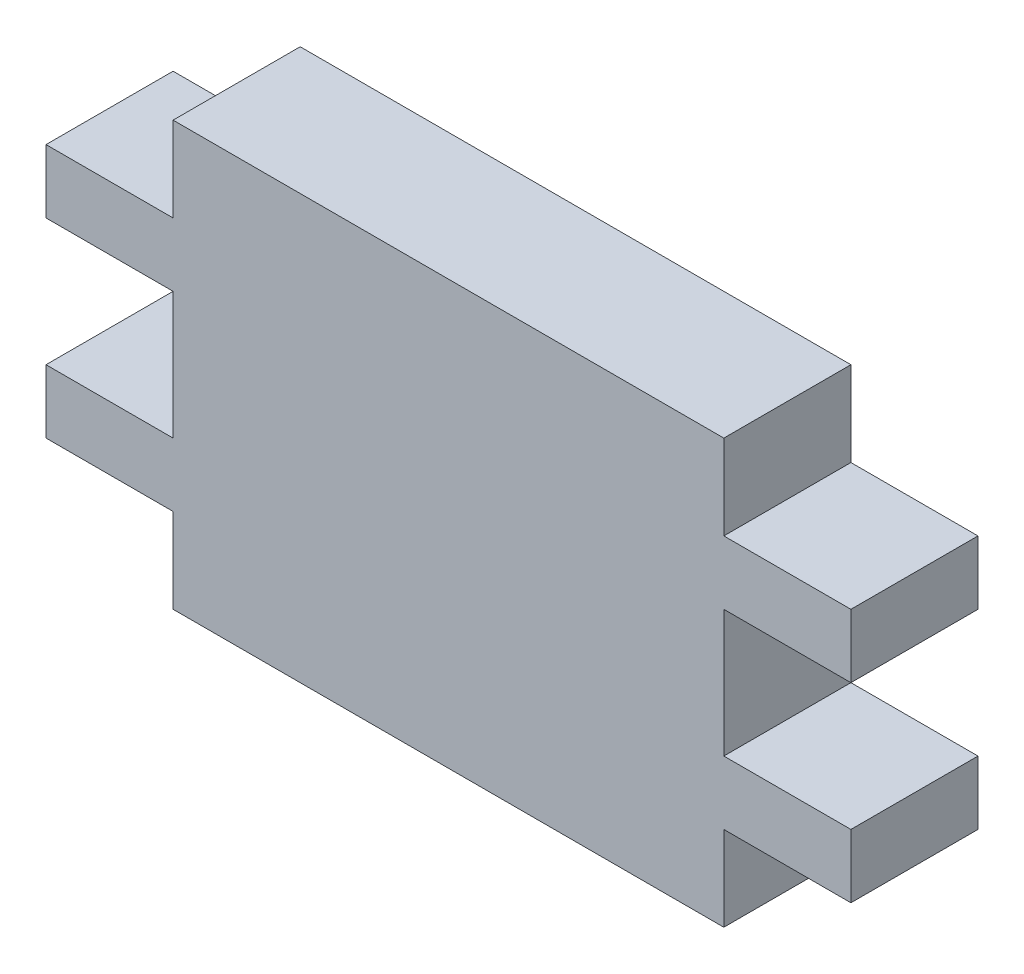
SolidWorks part; units mm, degrees
ref_plane "Plan de face" through (0, 0, 0) normal (0, 0, 1) x (1, 0, 0)
ref_plane "Plan de dessus" through (0, 0, 0) normal (0, 1, 0) x (1, 0, 0)
ref_plane "Plan de droite" through (0, 0, 0) normal (1, 0, 0) x (0, 0, -1)
sketch "Sketch1" plane through (0, 0, 0) normal (0, 0, 1) x (1, 0, 0)
  line L1 (-9.5, -5) -> (9.5, -5)
  line L2 (-9.5, -5) -> (-9.5, 5)
  line L3 (-9.5, 5) -> (9.5, 5)
  line L4 (9.5, -5) -> (9.5, 5)
  line L5 (-9.5, -5) -> (9.5, 5) construction
  line L6 (-9.5, 5) -> (9.5, -5) construction
  point P0 (0, 0)
  dimension "D1" = 19
  dimension "D2" = 10
extrude "Boss-Extrude1" add sketch "Sketch1" along normal blind 3
sketch "Sketch2" plane through (0, 0, 3) normal (0, 0, 1) x (1, 0, 0)
  line L0 (-9.5, 5) -> (-9.5, -5) construction
  line L1 (-9.5, 3) -> (-6.5, 3)
  line L2 (-9.5, 3) -> (-9.5, 5)
  line L3 (-9.5, 5) -> (-6.5, 5)
  line L4 (-6.5, 3) -> (-6.5, 5)
  line L5 (9.5, 5) -> (-9.5, 5) construction
  line L7 (-9.5, 1.5) -> (-6.5, 1.5)
  line L8 (-9.5, 1.5) -> (-9.5, -1.5)
  line L9 (-9.5, -1.5) -> (-6.5, -1.5)
  line L10 (-6.5, 1.5) -> (-6.5, -1.5)
  line L11 (-9.5, -3) -> (-6.5, -3)
  line L12 (-9.5, -3) -> (-9.5, -5)
  line L13 (-9.5, -5) -> (-6.5, -5)
  line L14 (-6.5, -3) -> (-6.5, -5)
  dimension "D1" = 2
  dimension "D2" = 3
  dimension "D3" = 1.5
  dimension "D4" = 3
  dimension "D5" = 3
  dimension "D6" = 3
  dimension "D7" = 2
  dimension "D8" = 1.5
extrude "Cut-Extrude1" cut sketch "Sketch2" against normal blind 3
sketch "Sketch3" plane through (0, 0, 3) normal (0, 0, 1) x (1, 0, 0)
  line L0 (9.5, 5) -> (-6.5, 5) construction
  line L1 (6.5, 5) -> (9.5, 5)
  line L2 (6.5, 5) -> (6.5, 3)
  line L3 (6.5, 3) -> (9.5, 3)
  line L4 (9.5, 5) -> (9.5, 3)
  line L5 (9.5, -5) -> (9.5, 5) construction
  line L7 (9.5, 1.5) -> (6.5, 1.5)
  line L8 (9.5, 1.5) -> (9.5, -1.5)
  line L9 (9.5, -1.5) -> (6.5, -1.5)
  line L10 (6.5, 1.5) -> (6.5, -1.5)
  line L11 (9.5, -3) -> (6.5, -3)
  line L12 (9.5, -3) -> (9.5, -5)
  line L13 (9.5, -5) -> (6.5, -5)
  line L14 (6.5, -3) -> (6.5, -5)
  point P16 (8, -3)
  dimension "D1" = 2
  dimension "D2" = 3
  dimension "D3" = 1.5
  dimension "D4" = 3
  dimension "D5" = 3
  dimension "D6" = 1.5
  dimension "D7" = 2
  dimension "D8" = 3
extrude "Cut-Extrude2" cut sketch "Sketch3" against normal blind 3
